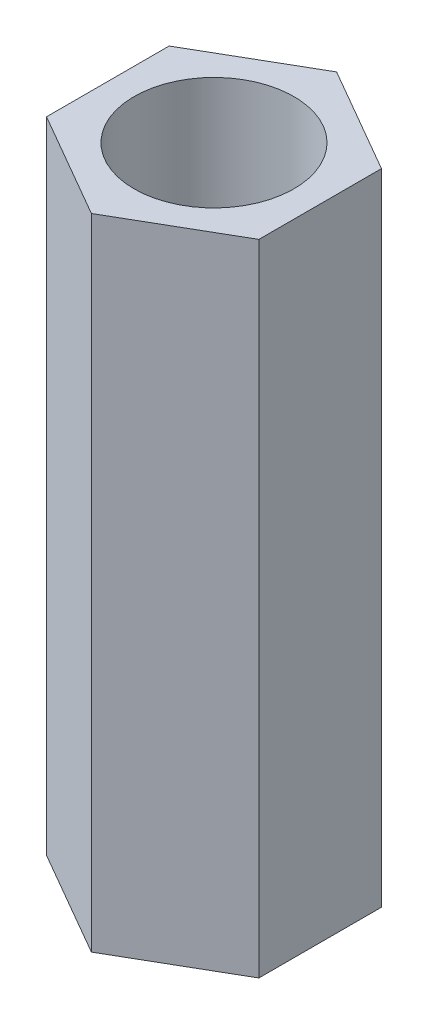
SolidWorks part; units mm, degrees
material "黄铜"
ref_plane "前视基准面" through (0, 0, 0) normal (0, 0, 1) x (1, 0, 0)
ref_plane "上视基准面" through (0, 0, 0) normal (0, 1, 0) x (1, 0, 0)
ref_plane "右视基准面" through (0, 0, 0) normal (1, 0, 0) x (0, 0, -1)
other "Configuration Table"
sketch "草图1" plane through (0, 0, 0) normal (0, 1, 0) x (1, 0, 0)
  line L0 (0, 0) -> (0, 3.0947) construction
  line L1 (1.9919, 1.15) -> (0, 2.3)
  line L2 (0, 2.3) -> (-1.9919, 1.15)
  line L3 (-1.9919, 1.15) -> (-1.9919, -1.15)
  line L4 (-1.9919, -1.15) -> (0, -2.3)
  line L5 (0, -2.3) -> (1.9919, -1.15)
  line L6 (1.9919, -1.15) -> (1.9919, 1.15)
  circle A0 centre (0, 0) radius 1.5
  circle A1 centre (0, 0) radius 1.9919 construction
  dimension "D1" = 3
  dimension "D2" = 4.6
extrude "凸台-拉伸1" add sketch "草图1" along normal blind 12
